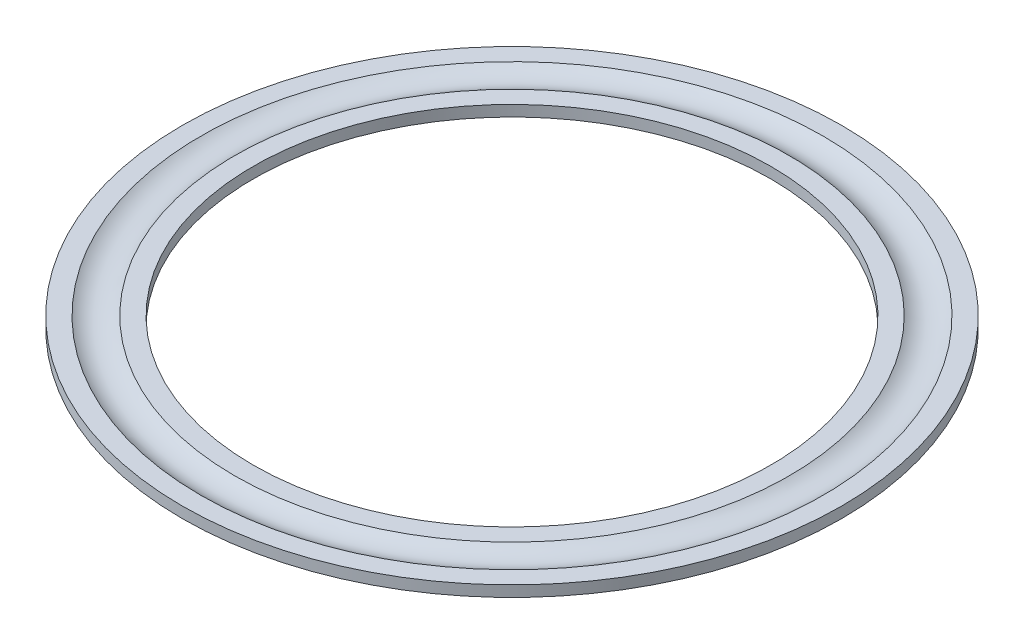
SolidWorks part; units mm, degrees
ref_plane "Front Plane" through (0, 0, 0) normal (0, 0, 1) x (1, 0, 0)
ref_plane "Top Plane" through (0, 0, 0) normal (0, 1, 0) x (1, 0, 0)
ref_plane "Right Plane" through (0, 0, 0) normal (1, 0, 0) x (0, 0, -1)
ref_plane "Plane1" through (0, 0, 0) normal (0, 0, -1) x (-1, 0, 0)
sketch "Sketch1" plane through (0, 0, 0) normal (0, 0, -1) x (-1, 0, 0)
  line L0 (-60.4, 0) -> (-47.4086, 0)
  line L3 (-47.4086, 2) -> (-50.8086, 2)
  line L4 (-57, 2) -> (-60.4, 2)
  line L7 (0, 0) -> (0, 6.8724) construction
  line L8 (-60.4, 0) -> (-60.4, 2)
  line L9 (-47.4086, 0) -> (-47.4086, 2)
  arc A1 (-50.8086, 2) -> (-57, 2) centre (-53.9043, 6.1276) cw
  dimension "D1" = 5.1595
  dimension "D2" = 2
  dimension "D3" = 6.1914
  dimension "D4" = 3.4
  dimension "D5" = 3.4
revolve "Revolve1" add sketch "Sketch1" angle 360 about L7
